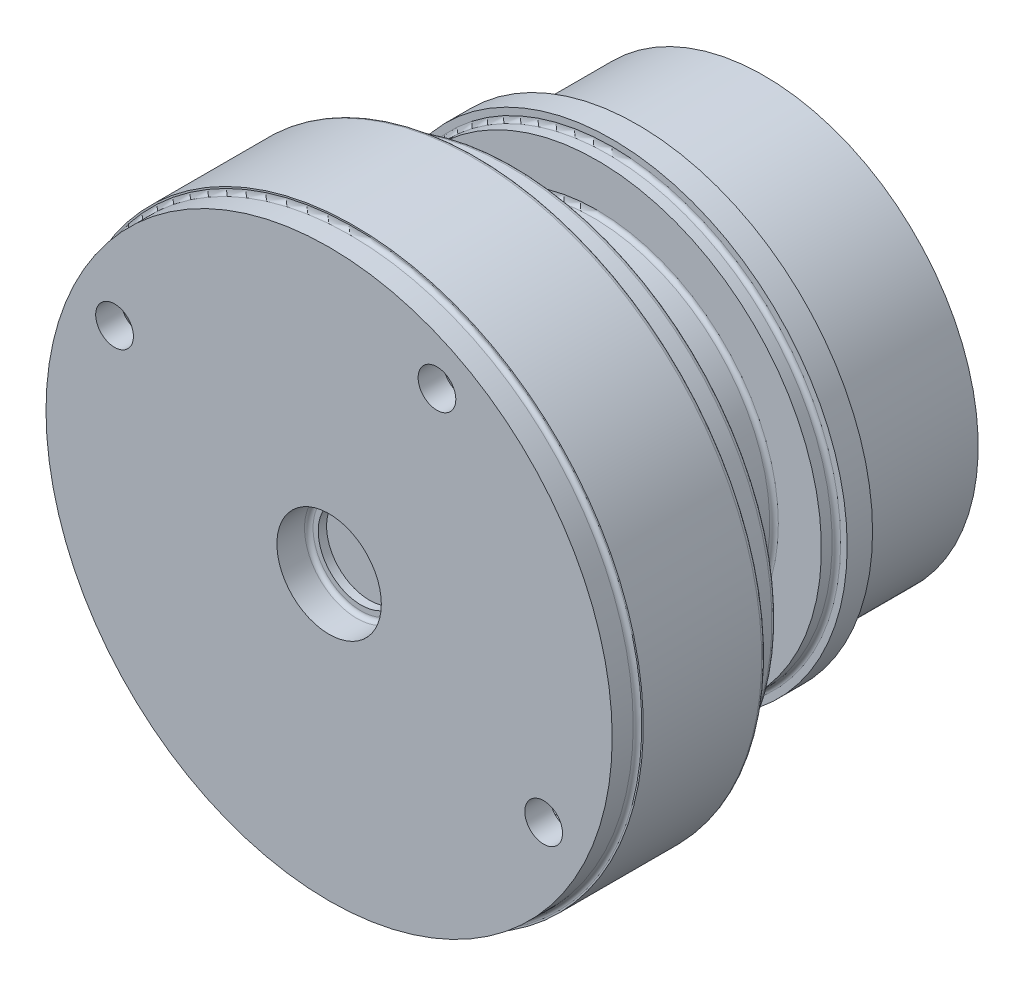
SolidWorks part; units mm, degrees
material "Ductile Iron (SN)"
ref_plane "Front Plane" through (0, 0, 0) normal (0, 0, 1) x (1, 0, 0)
ref_plane "Top Plane" through (0, 0, 0) normal (0, 1, 0) x (1, 0, 0)
ref_plane "Right Plane" through (0, 0, 0) normal (1, 0, 0) x (0, 0, -1)
sketch "Sketch1" plane through (0, 0, 0) normal (0, 0, 1) x (1, 0, 0)
  circle A0 centre (0, 0) radius 168
  circle A1 centre (-127.3203, 63.9984) radius 11.19
  circle A2 centre (63.9984, 127.3203) radius 11.19
  circle A3 centre (127.3203, -63.9984) radius 11.19
  circle A4 centre (-63.9984, -127.3203) radius 11.19 construction
  circle A5 centre (0, 0) radius 142.5 construction
  dimension "D1" = 336
  dimension "D2" = 142.5
extrude "Boss-Extrude1" add sketch "Sketch1" against normal blind 15
sketch "Sketch2" plane through (0, 0, -15) normal (0, 0, -1) x (-1, 0, 0)
  circle A0 centre (0, 0) radius 171.45
  dimension "D1" = 342.9
extrude "Boss-Extrude2" add sketch "Sketch2" along normal blind 94.6
sketch "Sketch3" plane through (0, 0, -109.6) normal (0, 0, -1) x (-1, 0, 0)
  circle A0 centre (0, 0) radius 105
  dimension "D1" = 210
extrude "Boss-Extrude3" add sketch "Sketch3" along normal blind 49.448
sketch "Sketch4" plane through (0, 0, -159.048) normal (0, 0, -1) x (-1, 0, 0)
  circle A0 centre (0, 0) radius 133.096
  dimension "D1" = 266.192
extrude "Boss-Extrude4" add sketch "Sketch4" along normal blind 8.904
sketch "Sketch5" plane through (0, 0, -167.952) normal (0, 0, -1) x (-1, 0, 0)
  circle A0 centre (0, 0) radius 139.5
  dimension "D1" = 279
extrude "Boss-Extrude5" add sketch "Sketch5" along normal blind 15.048
sketch "Sketch6" plane through (0, 0, -183) normal (0, 0, -1) x (-1, 0, 0)
  circle A0 centre (0, 0) radius 127
  dimension "D1" = 254
ref_plane "Plane1" through (0, 171.45, 0) normal (0, 1, 0) x (1, 0, 0)
extrude "Boss-Extrude10" add sketch "Sketch6" along normal blind 75.18
sketch "Sketch11" plane through (0, 0, 0) normal (0, 0, 1) x (1, 0, 0)
  circle A0 centre (0, 0) radius 25.4
  dimension "D1" = 50.8
extrude "Cut-Extrude1" cut sketch "Sketch11" against normal through all
sketch "Sketch12" plane through (0, 0, 0) normal (0, 0, 1) x (1, 0, 0)
  circle A0 centre (0, 0) radius 30.988
  dimension "D1" = 61.976
extrude "Cut-Extrude2" cut sketch "Sketch12" against normal blind 18.923
ref_plane "Plane2" through (0, -171.45, 0) normal (0, -1, 0) x (-1, 0, 0)
sketch "Sketch13" plane through (0, 0, -258.18) normal (0, 0, -1) x (-1, 0, 0)
  circle A0 centre (0, 0) radius 30.988
  dimension "D1" = 61.976
extrude "Cut-Extrude3" cut sketch "Sketch13" against normal blind 17.78
shell "Shell2" [suppressed] thickness 2.54
sketch "Sketch14" plane through (0, 0, 0) normal (0, 1, 0) x (1, 0, 0)
  line L0 (19.6475, 234.5398) -> (35.5644, 234.5398)
  line L1 (96.4965, 234.5398) -> (96.4965, 101.4187)
  line L2 (147.9257, 79.096) -> (165.1383, 79.096)
  line L3 (165.1383, 79.096) -> (165.1383, 15)
  line L4 (-168, 15) -> (168, 15) construction
  line L5 (165.1383, 15) -> (38.3002, 15)
  line L6 (38.3002, 15) -> (38.3002, 23.8889)
  line L7 (38.3002, 23.8889) -> (19.6475, 23.8889)
  line L8 (19.6475, 23.8889) -> (19.6475, 234.5398)
  line L9 (0, 258.18) -> (0, 0) construction
  line L10 (30.988, 258.18) -> (-30.988, 258.18) construction
  line L11 (35.5644, 234.5398) -> (35.5644, 247.2236)
  line L12 (35.5644, 247.2236) -> (96.4965, 247.2236)
  line L13 (96.4965, 247.2236) -> (96.4965, 234.5398)
  line L14 (147.9257, 79.096) -> (147.9257, 101.4187)
  line L15 (147.9257, 101.4187) -> (96.4965, 101.4187)
revolve "Cut-Revolve1" cut sketch "Sketch14" angle 360 about L9
fillet "Fillet1" radius 2.54 8 edges at (30.988, 0, -18.923) (-30.988, 0, -240.4) (-168, 0, -15) (-171.45, 0, -109.6) (-105, 0, -109.6) (-133.096, 0, -167.952) (-127, 0, -183) (-105, 0, -159.048)
fillet "Fillet2" radius 2.54 3 edges at (-165.1383, 0, -15) (-96.4965, 0, -247.2236) (-165.1383, 0, -79.096)
fillet "Fillet3" radius 2.54 4 edges at (-38.3002, 0, -23.8889) (-35.5644, 0, -234.5398) (-35.5644, 0, -247.2236) (-38.3002, 0, -15)
sketch "Sketch16" plane through (0, 0, 0) normal (1, 0, 0) x (0, 0, -1)
  line L0 (0, 0) -> (258.18, 0) construction
  line L1 (87.8108, 187.1761) -> (126.3092, 187.1761)
  line L2 (87.8108, 187.1761) -> (87.8108, 155.7239)
  line L3 (87.8108, 155.7239) -> (126.3092, 155.7239)
  line L4 (126.3092, 187.1761) -> (126.3092, 155.7239)
  line L5 (87.8108, 187.1761) -> (126.3092, 155.7239) construction
  line L6 (87.8108, 155.7239) -> (126.3092, 187.1761) construction
  line L7 (258.18, -127) -> (258.18, 127) construction
  point P0 (107.06, 171.45)
revolve "Cut-Revolve2" cut sketch "Sketch16" angle 360 about L0
fillet "Fillet4" radius 2.54 3 edges at (-96.4965, 0, -101.4187) (-147.9257, 0, -79.096) (-147.9257, 0, -101.4187)
fillet "Fillet5" radius 2.54 3 edges at (-171.45, 0, -87.8108) (155.7239, 0, -87.8108) (-155.7239, 0, -109.6)
